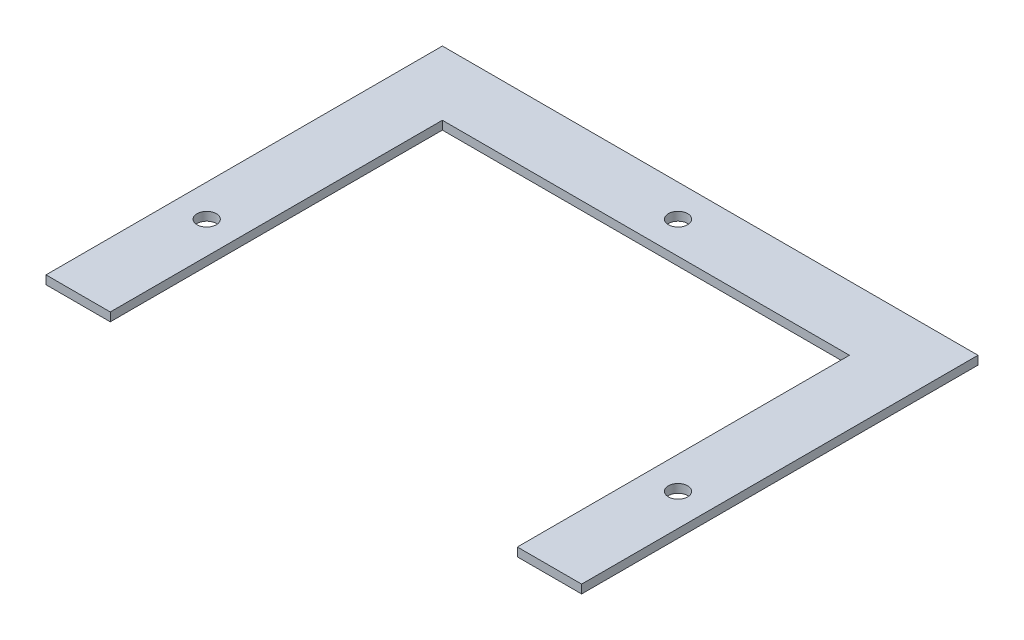
SolidWorks part; units mm, degrees
material "Galvanized Steel"
ref_plane "Front Plane" through (0, 0, 0) normal (0, 0, 1) x (1, 0, 0)
ref_plane "Top Plane" through (0, 0, 0) normal (0, 1, 0) x (1, 0, 0)
ref_plane "Right Plane" through (0, 0, 0) normal (1, 0, 0) x (0, 0, -1)
sketch "Sketch1" plane through (0, 0, 0) normal (0, 1, 0) x (1, 0, 0)
  line L1 (-95, -112.5) -> (95, -112.5)
  line L2 (-95, -112.5) -> (-95, 112.5)
  line L3 (-95, 112.5) -> (95, 112.5)
  line L4 (95, -112.5) -> (95, 112.5)
  line L5 (-95, -112.5) -> (95, 112.5) construction
  line L6 (-95, 112.5) -> (95, -112.5) construction
  point P0 (0, 0)
  dimension "D1" = 190
  dimension "D2" = 225
extrude "Extrude-Thin1" add sketch "Sketch1" along normal blind 4 thin
sketch "Sketch2" plane through (0, 0, 0) normal (0, -1, 0) x (1, 0, 0)
  line L0 (125, 142.5) -> (125, -142.5) construction
  line L1 (-125, 142.5) -> (125, 142.5)
  line L2 (-125, 142.5) -> (-125, 42.5)
  line L3 (-125, 42.5) -> (125, 42.5)
  line L4 (125, 142.5) -> (125, 42.5)
  line L5 (95, -112.5) -> (-95, -112.5) construction
  dimension "D1" = 155
extrude "Cut-Extrude1" cut sketch "Sketch2" against normal blind 10
sketch "Sketch3" plane through (0, 0, 0) normal (0, -1, 0) x (1, 0, 0)
  line L0 (95, -112.5) -> (-95, -112.5) construction
  circle A0 centre (0, -127.5) radius 4.5
  dimension "D1" = 9
  dimension "D2" = 15
extrude "Cut-Extrude2" cut sketch "Sketch3" against normal blind 10
pattern_linear "LPattern1" count 2 spacing 144.5 along (-1, 0, 0) count 2 spacing 144.5 along (-1, 0, 0) of "Cut-Extrude2"
sketch "Sketch4" plane through (0, 0, 0) normal (0, -1, 0) x (-1, 0, 0)
  line L0 (95, 112.5) -> (95, -42.5) construction
  circle A0 centre (110, 17.5) radius 4.5
  dimension "D2" = 15
extrude "Cut-Extrude3" cut sketch "Sketch4" against normal blind 10
mirror "Mirror1" about plane through (0, 0, 0) normal (1, 0, 0) of "Cut-Extrude3"
